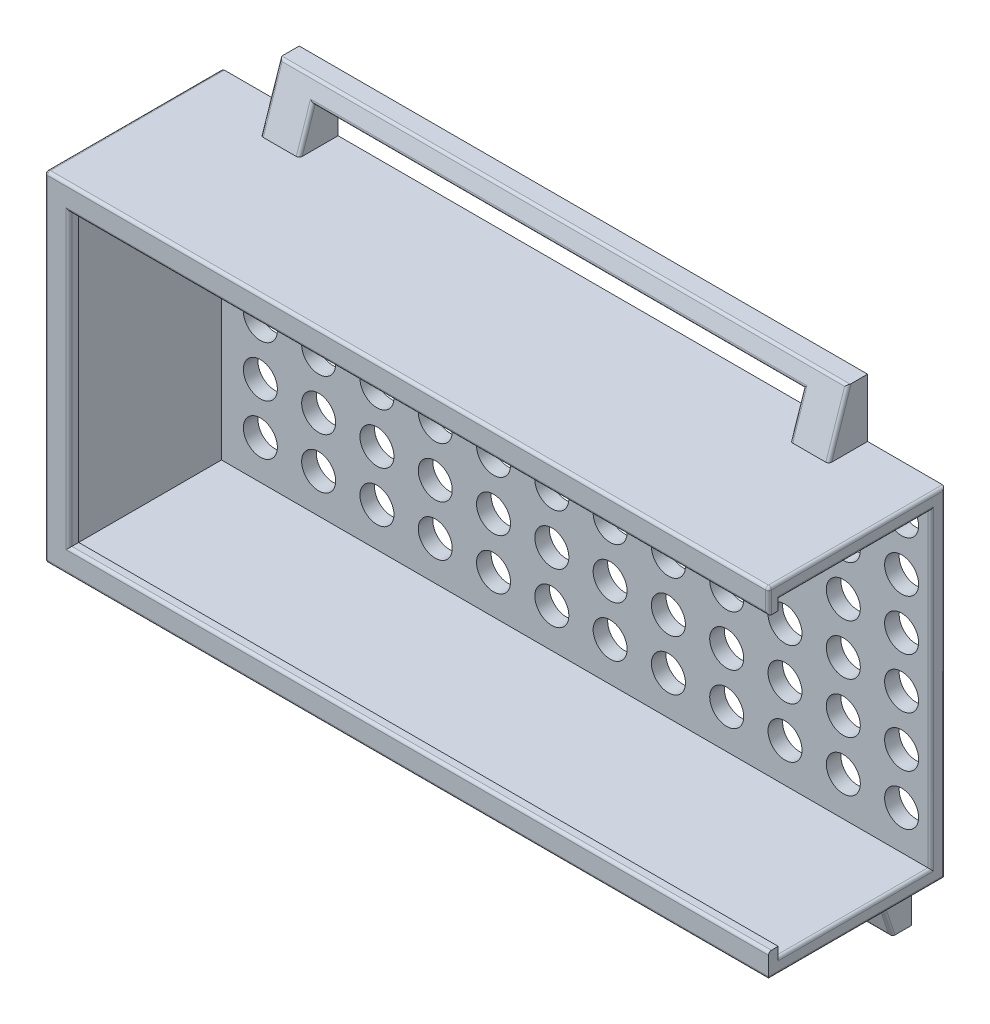
SolidWorks part; units mm, degrees
ref_plane "前视基准面" through (0, 0, 0) normal (0, 0, 1) x (1, 0, 0)
ref_plane "上视基准面" through (0, 0, 0) normal (0, 1, 0) x (1, 0, 0)
ref_plane "右视基准面" through (0, 0, 0) normal (1, 0, 0) x (0, 0, -1)
sketch "草图1" plane through (0, 0, 0) normal (0, 0, 1) x (1, 0, 0)
  line L0 (-1.5, -1.5) -> (-1.5, 33.4)
  line L1 (0, 0) -> (71.5, 0)
  line L2 (0, 0) -> (0, 31.9)
  line L3 (0, 31.9) -> (71.5, 31.9)
  line L4 (71.5, 0) -> (71.5, 31.9)
  line L5 (-1.5, 33.4) -> (73, 33.4)
  line L6 (73, -1.5) -> (73, 33.4)
  line L7 (-1.5, -1.5) -> (73, -1.5)
  dimension "D1" = 71.5
  dimension "D2" = 31.9
  dimension "D3" = 1.5
extrude "凸台-拉伸1" add sketch "草图1" along normal blind 18.2
sketch "草图2" plane through (0, 0, 0) normal (0, 0, -1) x (-1, 0, 0)
  line L4 (0, 0) -> (0, 31.9)
  line L5 (-71.5, 0) -> (0, 0)
  line L6 (-71.5, 31.9) -> (-71.5, 0)
  line L7 (0, 31.9) -> (-71.5, 31.9)
  line L8 (0, 0) -> (0, 31.9)
  line L9 (-71.5, 0) -> (0, 0)
  line L10 (-71.5, 31.9) -> (-71.5, 0)
  line L11 (0, 31.9) -> (-71.5, 31.9)
  dimension "D1" = 0
extrude "凸台-拉伸2" add sketch "草图2" against normal blind 1.5
sketch "草图3" plane through (71.5, 0, 0) normal (-1, 0, 0) x (0, 0, 1)
  line L4 (18.2, 31.9) -> (1.5, 31.9)
  line L5 (1.5, 31.9) -> (1.5, 0)
  line L6 (1.5, 0) -> (18.2, 0)
  line L7 (18.2, 0) -> (18.2, 31.9)
  line L8 (18.2, 31.9) -> (1.5, 31.9)
  line L9 (1.5, 31.9) -> (1.5, 0)
  line L10 (1.5, 0) -> (18.2, 0)
  line L11 (18.2, 0) -> (18.2, 31.9)
  dimension "D1" = 0
extrude "切除-拉伸1" cut sketch "草图3" against normal through all
sketch "草图4" plane through (0, 0, 18.2) normal (0, 0, 1) x (1, 0, 0)
  line L3 (0, 0) -> (73, 0) construction
  line L4 (0, 31.9) -> (0, 0) construction
  line L5 (73, 31.9) -> (0, 31.9) construction
  line L6 (1, 1) -> (73, 1)
  line L7 (1, 30.9) -> (1, 1)
  line L8 (73, 30.9) -> (1, 30.9)
  line L9 (1, 1) -> (73, 1)
  line L10 (1, 30.9) -> (1, 1)
  line L11 (73, 30.9) -> (1, 30.9)
  line L12 (0, 0) -> (73, 0)
  line L13 (0, 31.9) -> (0, 0)
  line L14 (73, 31.9) -> (0, 31.9)
  line L15 (73, 30.9) -> (73, 31.9)
  line L16 (73, 1) -> (73, 0)
  dimension "D1" = 1
extrude "凸台-拉伸3" add sketch "草图4" against normal blind 1
sketch "草图5" plane through (0, 33.4, 0) normal (0, 1, 0) x (1, 0, 0)
  line L0 (35.75, 0) -> (35.75, -18.2) construction
  line L1 (6.5, 0) -> (10.5, 0)
  line L2 (6.5, 0) -> (6.5, -4)
  line L3 (6.5, -4) -> (10.5, -4)
  line L4 (10.5, 0) -> (10.5, -4)
  line L5 (73, 0) -> (-1.5, 0) construction
  line L6 (73, -18.2) -> (-1.5, -18.2) construction
  line L7 (65, -4) -> (61, -4)
  line L8 (61, 0) -> (61, -4)
  line L9 (65, 0) -> (61, 0)
  line L10 (65, 0) -> (65, -4)
  line L11 (-1.5, -18.2) -> (-1.5, 0) construction
  line L12 (8.5, 0) -> (8.5, -4) construction
  dimension "D1" = 4
  dimension "D2" = 4
  dimension "D3" = 8
extrude "凸台-拉伸5" add sketch "草图5" along normal blind 6
sketch "草图15" plane through (61, 0, 0) normal (-1, 0, 0) x (0, 0, 1)
  line L0 (0, 39.4) -> (4, 39.4) construction
  line L1 (0, 39.4) -> (4, 39.4)
  line L2 (0, 39.4) -> (0, 37.4)
  line L3 (0, 39.4) -> (0, 33.4) construction
  line L4 (0, 37.4) -> (4, 37.4)
  line L5 (4, 39.4) -> (4, 33.4) construction
  line L6 (4, 37.4) -> (4, 39.4)
  dimension "D1" = 2
extrude "凸台-拉伸6" add sketch "草图15" along normal up to next
sketch "草图16" plane through (65, 0, 0) normal (1, 0, 0) x (0, 0, -1)
  line L0 (-4, 33.4) -> (-2, 39.4)
  line L1 (-4, 39.4) -> (0, 39.4) construction
  line L2 (-2, 39.4) -> (-4, 39.4)
  line L3 (-4, 39.4) -> (-4, 33.4)
extrude "切除-拉伸2" cut sketch "草图16" against normal through all
sketch "草图17" plane through (0, -1.5, 0) normal (0, -1, 0) x (1, 0, 0)
  line L2 (-1.5, 0) -> (73, 0) construction
  line L3 (2, 0) -> (6, 0)
  line L4 (2, 0) -> (2, 4)
  line L5 (2, 4) -> (6, 4)
  line L6 (6, 0) -> (6, 4)
  line L7 (35.75, 0) -> (35.75, 18.2) construction
  line L8 (-1.5, 18.2) -> (73, 18.2) construction
  line L9 (69.5, 4) -> (65.5, 4)
  line L10 (65.5, 0) -> (65.5, 4)
  line L11 (69.5, 0) -> (65.5, 0)
  line L12 (69.5, 0) -> (69.5, 4)
  dimension "D1" = 2
  dimension "D2" = 4
  dimension "D3" = 4
extrude "凸台-拉伸7" add sketch "草图17" along normal blind 6
sketch "草图18" plane through (65.5, 0, 0) normal (-1, 0, 0) x (0, 0, 1)
  line L0 (0, -7.5) -> (0, -5.5)
  line L1 (0, -7.5) -> (0, -1.5) construction
  line L2 (0, -5.5) -> (4, -5.5)
  line L3 (4, -7.5) -> (4, -1.5) construction
  line L4 (4, -5.5) -> (4, -7.5)
  line L5 (4, -7.5) -> (0, -7.5)
  dimension "D1" = 2
extrude "凸台-拉伸8" add sketch "草图18" along normal up to next
sketch "草图19" plane through (2, 0, 0) normal (-1, 0, 0) x (0, 0, 1)
  line L0 (4, -1.5) -> (2, -7.5)
  line L1 (4, -7.5) -> (0, -7.5) construction
  line L2 (2, -7.5) -> (4, -7.5)
  line L3 (4, -7.5) -> (4, -1.5)
extrude "切除-拉伸3" cut sketch "草图19" against normal through all
fillet "圆角1" radius 0.3 28 edges at (-1.5, 33.4, 9.1) (-1.5, 15.95, 18.2) (-1.5, -1.5, 9.1) (-1.5, 15.95, 0) (73, 31.9, 9.35) (73, 15.95, 1.5) (73, 0, 9.35) (73, -1.5, 9.1) (1, 15.95, 18.2) (37, 1, 18.2) (35.75, -1.5, 18.2) (73, 15.95, 0) (73, 32.15, 18.2) (37, 30.9, 18.2) (73, 33.4, 9.1) (35.75, 33.4, 18.2) (10.5, 35.4, 3.3333) (35.75, 37.4, 2.6667) (61, 35.4, 3.3333) (6, -3.5, 3.3333) (35.75, -5.5, 2.6667) (65.5, -3.5, 3.3333) (69.5, -4.5, 3) (35.75, -7.5, 2) (2, -4.5, 3) (65, 36.4, 3) (35.75, 39.4, 2) (6.5, 36.4, 3)
sketch "草图20" plane through (0, 0, 1.5) normal (0, 0, 1) x (1, 0, 0)
  line L0 (4, 4) -> (10, 4) construction
  line L1 (4, 4) -> (4, 9.2) construction
  line L2 (4, 30) -> (10, 30) construction
  circle A0 centre (4, 4) radius 1.75
  circle A1 centre (10, 4) radius 1.75
  circle A2 centre (16, 4) radius 1.75
  circle A3 centre (22, 4) radius 1.75
  circle A4 centre (28, 4) radius 1.75
  circle A5 centre (34, 4) radius 1.75
  circle A6 centre (40, 4) radius 1.75
  circle A7 centre (46, 4) radius 1.75
  circle A8 centre (52, 4) radius 1.75
  circle A9 centre (58, 4) radius 1.75
  circle A10 centre (64, 4) radius 1.75
  circle A11 centre (70, 4) radius 1.75
  circle A12 centre (4, 9.2) radius 1.75
  circle A13 centre (4, 14.4) radius 1.75
  circle A14 centre (4, 19.6) radius 1.75
  circle A15 centre (4, 24.8) radius 1.75
  circle A16 centre (4, 30) radius 1.75
  circle A17 centre (10, 30) radius 1.75
  circle A18 centre (10, 24.8) radius 1.75
  circle A19 centre (10, 19.6) radius 1.75
  circle A20 centre (10, 14.4) radius 1.75
  circle A21 centre (10, 9.2) radius 1.75
  circle A22 centre (16, 30) radius 1.75
  circle A23 centre (16, 24.8) radius 1.75
  circle A24 centre (16, 19.6) radius 1.75
  circle A25 centre (16, 14.4) radius 1.75
  circle A26 centre (16, 9.2) radius 1.75
  circle A27 centre (22, 30) radius 1.75
  circle A28 centre (22, 24.8) radius 1.75
  circle A29 centre (22, 19.6) radius 1.75
  circle A30 centre (22, 14.4) radius 1.75
  circle A31 centre (22, 9.2) radius 1.75
  circle A32 centre (28, 30) radius 1.75
  circle A33 centre (28, 24.8) radius 1.75
  circle A34 centre (28, 19.6) radius 1.75
  circle A35 centre (28, 14.4) radius 1.75
  circle A36 centre (28, 9.2) radius 1.75
  circle A37 centre (34, 30) radius 1.75
  circle A38 centre (34, 24.8) radius 1.75
  circle A39 centre (34, 19.6) radius 1.75
  circle A40 centre (34, 14.4) radius 1.75
  circle A41 centre (34, 9.2) radius 1.75
  circle A42 centre (40, 30) radius 1.75
  circle A43 centre (40, 24.8) radius 1.75
  circle A44 centre (40, 19.6) radius 1.75
  circle A45 centre (40, 14.4) radius 1.75
  circle A46 centre (40, 9.2) radius 1.75
  circle A47 centre (46, 30) radius 1.75
  circle A48 centre (46, 24.8) radius 1.75
  circle A49 centre (46, 19.6) radius 1.75
  circle A50 centre (46, 14.4) radius 1.75
  circle A51 centre (46, 9.2) radius 1.75
  circle A52 centre (52, 30) radius 1.75
  circle A53 centre (52, 24.8) radius 1.75
  circle A54 centre (52, 19.6) radius 1.75
  circle A55 centre (52, 14.4) radius 1.75
  circle A56 centre (52, 9.2) radius 1.75
  circle A57 centre (58, 30) radius 1.75
  circle A58 centre (58, 24.8) radius 1.75
  circle A59 centre (58, 19.6) radius 1.75
  circle A60 centre (58, 14.4) radius 1.75
  circle A61 centre (58, 9.2) radius 1.75
  circle A62 centre (64, 30) radius 1.75
  circle A63 centre (64, 24.8) radius 1.75
  circle A64 centre (64, 19.6) radius 1.75
  circle A65 centre (64, 14.4) radius 1.75
  circle A66 centre (64, 9.2) radius 1.75
  circle A67 centre (70, 30) radius 1.75
  circle A68 centre (70, 24.8) radius 1.75
  circle A69 centre (70, 19.6) radius 1.75
  circle A70 centre (70, 14.4) radius 1.75
  circle A71 centre (70, 9.2) radius 1.75
  dimension "D1" = 4
  dimension "D2" = 4
  dimension "D3" = 3.5
  dimension "D4" = 12
  dimension "D5" = 6
  dimension "D6" = 5.2
  dimension "D8" = 6
  dimension "D7" = 6
extrude "切除-拉伸4" cut sketch "草图20" against normal through all
